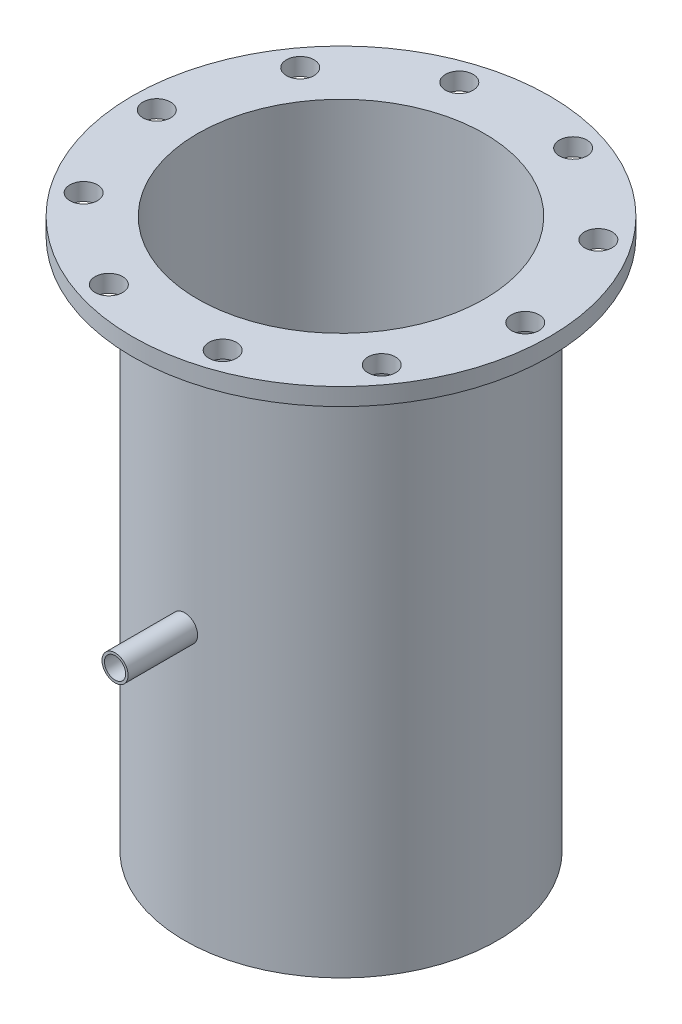
SolidWorks part; units mm, degrees
other "DetailItem1"
other "DetailItem2"
other "Weld Folder"
other "Weld Bead1"
other "Weld Bead2"
material "1023 Carbon Steel Sheet (SS)"
ref_plane "Front Plane" through (0, 0, 0) normal (0, 0, 1) x (1, 0, 0)
ref_plane "Top Plane" through (0, 0, 0) normal (0, 1, 0) x (1, 0, 0)
ref_plane "Right Plane" through (0, 0, 0) normal (1, 0, 0) x (0, 0, -1)
sketch "Sketch1" plane through (0, 0, 0) normal (0, 0, 1) x (1, 0, 0)
  line L0 (0, 0) -> (0, -134.8652) construction
  line L1 (52.3875, 0) -> (52.3875, -170.8058)
  line L2 (52.3875, -200.6) -> (57.15, -200.6)
  line L3 (57.15, -200.6) -> (57.15, -8.89)
  line L4 (54.61, -6.35) -> (76.2, -6.35)
  line L5 (76.2, -6.35) -> (76.2, 0)
  line L6 (76.2, 0) -> (52.3875, 0)
  line L7 (52.3875, -188.027) -> (53.848, -188.027)
  line L8 (53.848, -188.027) -> (53.848, -191.075)
  line L9 (53.848, -191.075) -> (52.3875, -191.075)
  line L10 (52.3875, -184.217) -> (54.9275, -184.217)
  line L11 (52.3875, -191.075) -> (52.3875, -200.6)
  line L12 (57.15, -8.89) -> (54.61, -6.35)
  line L13 (54.9275, -184.217) -> (54.9275, -179.4164)
  line L14 (54.9275, -179.4164) -> (52.3875, -179.4164)
  line L15 (-56.1848, -191.075) -> (56.1848, -191.075) construction
  line L16 (-50.1022, -191.075) -> (50.1022, -191.075) construction
  line L17 (52.3875, -184.217) -> (52.3875, -188.027)
  line L18 (52.3875, -175.6064) -> (54.9275, -175.6064)
  line L19 (54.9275, -175.6064) -> (54.9275, -170.8058)
  line L20 (54.9275, -170.8058) -> (52.3875, -170.8058)
  line L21 (52.3875, -175.6064) -> (52.3875, -179.4164)
  dimension "D1" = 52.3875
  dimension "D2" = 57.15
  dimension "D3" = 76.2
  dimension "D4" = 6.35
  dimension "D5" = 9.525
  dimension "D6" = 53.848
  dimension "D7" = 3.048
  dimension "D8" = 3.81
  dimension "D9" = 45
  dimension "D10" = 2.54
  dimension "D11" = 4.8006
  dimension "D12" = 2.54
revolve "Revolve1" add sketch "Sketch1" angle 360 about L0
hole_wizard "Tap Drill for 3/8-16 Tap1" positions "Sketch2" profile "Sketch3" hole size "3/8" standard "ANSI Inch" end condition through all
sketch "Sketch2" plane through (0, 0, 0) normal (0, 1, 0) x (1, 0, 0)
  point P1 (67.31, 0)
  dimension "D1" = 67.31
sketch "Sketch3" plane through (67.31, 0, 0) normal (1, 0, 0) x (0, 0, 1)
  line L0 (0, 0) -> (0, 200.6)
  line L1 (0, 200.6) -> (5.0419, 200.6)
  line L2 (5.0419, 200.6) -> (5.0419, 0)
  line L5 (5.0419, 0) -> (0, 0)
  line L11 (0, -6.35) -> (0, 107.95) construction
  dimension "Thru Hole Dia." = 10.0838
  dimension "Thru Hole Depth" = 200.6
pattern_circular "CirPattern1" count 10 over 360 about axis through (0, 0, 0) along (0, 1, 0) of "Tap Drill for 3/8-16 Tap1"
ref_plane "Plane1" through (0, 0, 57.15) normal (0, 0, 1) x (1, 0, 0)
sketch "Sketch4" plane through (0, 0, 57.15) normal (0, 0, 1) x (1, 0, 0)
  circle A0 centre (0, -101.6) radius 4.7625
  circle A1 centre (0, -101.6) radius 3.8735
  dimension "D1" = 9.525
  dimension "D2" = 0.889
  dimension "D3" = 101.6
extrude "Boss-Extrude1" add sketch "Sketch4" along normal blind 25.4 separate body
hole_wizard "1/8 (0.125) Diameter Hole3" positions "3DSketch2" profile "Sketch11" hole size "1/8" standard "ANSI Inch"
sketch3d "3DSketch2"
  circle A0 centre (0, -101.6, 57.15) radius 4.1349 construction
  circle A1 centre (0, -101.6, 57.15) radius 4.7625 construction
  point P6 (0, -101.6, 61.2849)
  point P19 (0, -101.6, 61.9125)
  point P21 (0, -101.6, 57.15)
sketch "Sketch11" plane through (0, -101.6, 57.15) normal (1, 0, 0) x (0, -1, 0)
  line L0 (0, 0) -> (0, 26.3539)
  line L1 (0, 26.3539) -> (1.5875, 25.4)
  line L2 (1.5875, 25.4) -> (1.5875, 0)
  line L5 (1.5875, 0) -> (0, 0)
  line L10 (0, 26.3539) -> (-1.5875, 25.4) construction
  line L11 (0, -6.35) -> (0, 107.95) construction
  dimension "Hole Dia." = 3.175
  dimension "Hole Depth" = 25.4
  dimension "Drill Angle" = 118
